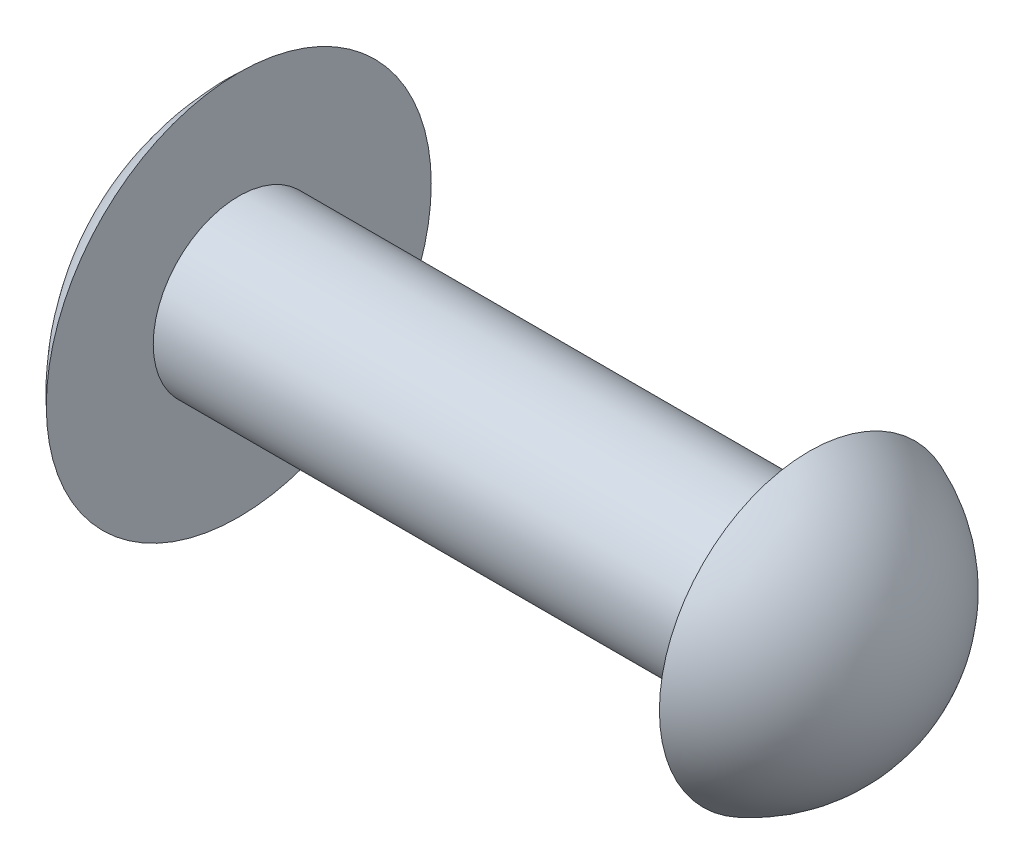
SolidWorks part; units mm, degrees
ref_plane "Plane1" through (0, 0, 0) normal (0, 0, 1) x (1, 0, 0)
ref_plane "Plane2" through (0, 0, 0) normal (0, 1, 0) x (1, 0, 0)
ref_plane "Plane3" through (0, 0, 0) normal (1, 0, 0) x (0, 0, -1)
sketch "Sketch1" plane through (0, 0, 0) normal (0, 0, 1) x (1, 0, 0)
  line L0 (-39, 0) -> (6, 0) construction
  line L1 (-23, 0) -> (0, 0)
  line L2 (-20, 3) -> (-20, 6.75)
  line L3 (-20, 3) -> (0, 3)
  line L4 (0, 3) -> (0, 0)
  arc A0 (-20, 6.75) -> (-23, 0) centre (-13.9063, 0) ccw
  point P12 (-20, 3)
  dimension "Diameter" = 6
  dimension "GripLength" = 20
  dimension "HeadHt" = 3
  dimension "HeadDia" = 13.5
revolve "Base-Revolve" add sketch "Sketch1" angle 360 about L0
sketch "Sketch2" plane through (0, 0, 0) normal (0, 0, 1) x (1, 0, 0)
  line L0 (-49, 0) -> (71, 0) construction
  line L1 (0, 0) -> (3.6, 0)
  line L2 (0, 0) -> (0, 5.25)
  arc A0 (3.6, 0) -> (0, 5.25) centre (-2.0281, 0) ccw
  dimension "HeadDiaA" = 10.5
  dimension "HeadHtA" = 3.6
revolve "HeadTypeA" add sketch "Sketch2" angle 360 about L0
sketch "Sketch3" plane through (0, 0, 0) normal (0, 0, 1) x (1, 0, 0)
  line L0 (30, 0) -> (-54, 0) construction
  line L1 (-39, 0) -> (6, 0) construction
  line L2 (0, 0) -> (0, 5.25)
  line L3 (0, 5.25) -> (-2.9323, 3)
  line L4 (-2.9323, 0) -> (0, 0)
  line L5 (0, -5.25) -> (-2.9323, -3) construction
  line L6 (-2.9323, 0) -> (-2.9323, 3)
  dimension "HeadDiaB" = 10.5
  dimension "D3" = 6
  dimension "D2" = 75
revolve "HeadTypeB" [suppressed] add sketch "Sketch3" angle 360 about L0
equation "\"D3@Sketch3\" = \"Diameter@Sketch1\""
